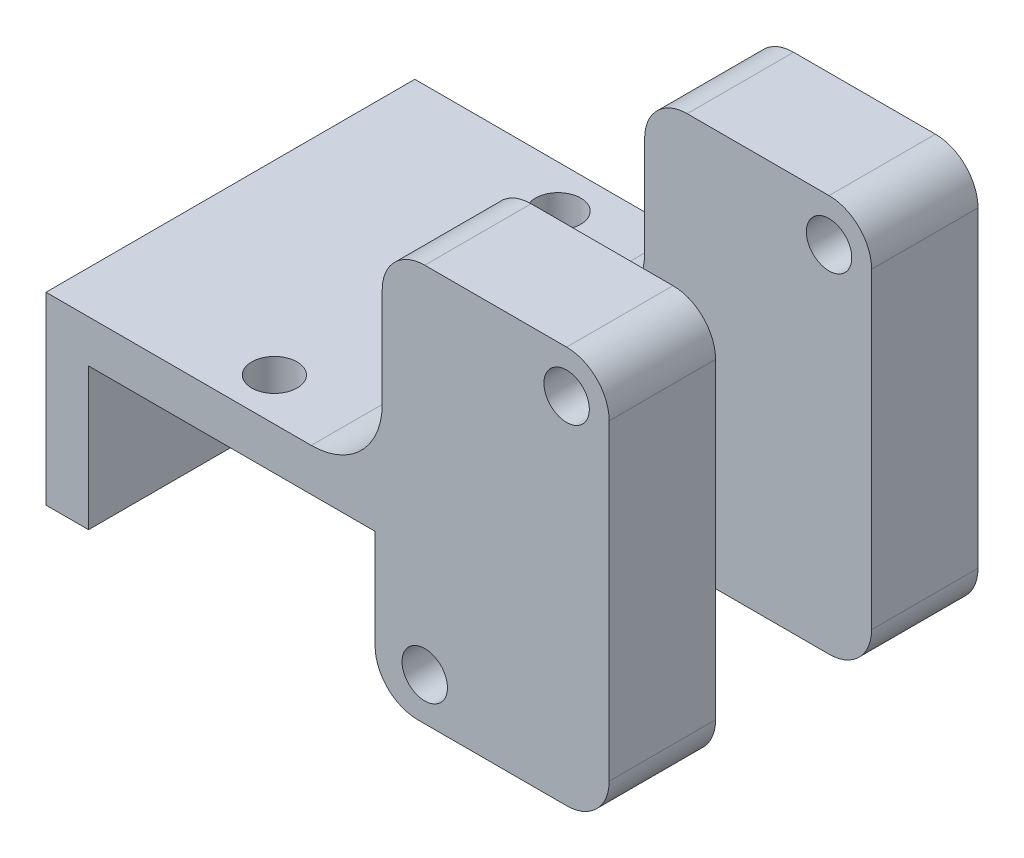
SolidWorks part; units mm, degrees
material "光敏树脂"
ref_plane "前视基准面" through (0, 0, 0) normal (0, 0, 1) x (1, 0, 0)
ref_plane "上视基准面" through (0, 0, 0) normal (0, 1, 0) x (1, 0, 0)
ref_plane "右视基准面" through (0, 0, 0) normal (1, 0, 0) x (0, 0, -1)
sketch "草图1" plane through (0, 0, 0) normal (0, 0, 1) x (1, 0, 0)
  line L0 (0, 96.72) -> (0, -75.892) construction
  line L1 (-70.2945, 0) -> (72.6376, 0) construction
  line L2 (-10.1, 0) -> (-10.1, 10)
  line L3 (-10.1, 10) -> (10.1, 10)
  line L4 (10.1, 10) -> (10.1, 0)
  line L5 (-13.1, 0) -> (-13.1, 13)
  line L6 (-13.1, 13) -> (10.6, 13)
  line L8 (-13.1, 0) -> (-10.1, 0)
  line L9 (10.1, 0) -> (13.1, 0)
  line L11 (13.1, 0) -> (26.6, 0)
  line L12 (13.1, 13) -> (13.1, 0) construction
  line L13 (26.6, 0) -> (26.6, 28)
  line L14 (26.6, 28) -> (10.6, 28)
  line L15 (10.6, 28) -> (10.6, 13)
  line L17 (-13.1, 13) -> (13.1, 13) construction
  circle A0 centre (23.6, 25) radius 1.6
  circle A1 centre (13.6, 3) radius 1.6
  point P14 (0, 10)
  dimension "D4" = 3.2
  dimension "D1" = 3
  dimension "D2" = 20.2
  dimension "D3" = 13
  dimension "D5" = 10
  dimension "D6" = 22
  dimension "D7" = 3.5
  dimension "D8" = 3
  dimension "D9" = 3
  dimension "D10" = 3
  dimension "D11" = 16
extrude "凸台-拉伸1" add sketch "草图1" along normal mid plane 26
sketch "草图2" plane through (0, 0, 0) normal (0, -1, 0) x (1, 0, 0)
  line L0 (-1.6961, 0) -> (30.7712, 0) construction
  line L1 (18.35, 13) -> (18.35, -13) construction
  line L2 (10.1, 13) -> (26.6, 13) construction
  line L3 (10.1, -13) -> (26.6, -13) construction
  line L4 (26.6, 13) -> (26.6, -13) construction
  line L5 (10.1, 5.5) -> (26.6, 5.5)
  line L6 (10.1, 5.5) -> (10.1, -5.5)
  line L7 (10.1, -5.5) -> (26.6, -5.5)
  line L8 (26.6, 5.5) -> (26.6, -5.5)
  line L9 (10.1, 5.5) -> (26.6, -5.5) construction
  line L10 (10.1, -5.5) -> (26.6, 5.5) construction
  point P9 (18.35, 0)
  dimension "D1" = 11
extrude "切除-拉伸1" cut sketch "草图2" against normal through all
sketch "草图3" plane through (0, 13, 0) normal (0, 1, 0) x (1, 0, 0)
  line L0 (-24.2443, 0) -> (24.6012, 0) construction
  line L1 (0, -20.9315) -> (0, 25.6558) construction
  circle A0 centre (0, 10) radius 1.6
  circle A1 centre (0, -10) radius 1.6
  dimension "D1" = 3.2
  dimension "D2" = 20
extrude "切除-拉伸2" cut sketch "草图3" against normal through all
fillet "圆角2" radius 5 1 edges at (10.6, 13, -9.25)
fillet "圆角3" radius 3 8 edges at (10.1, 0, -9.25) (26.6, 0, -9.25) (26.6, 28, -9.25) (10.6, 28, -9.25) (10.6, 28, 9.25) (26.6, 28, 9.25) (26.6, 0, 9.25) (10.1, 0, 9.25)
